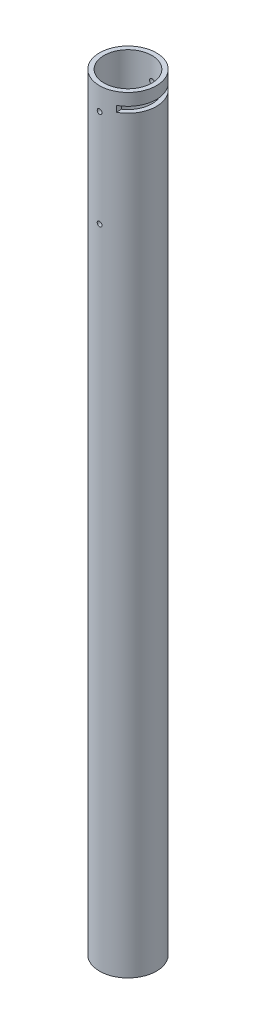
SolidWorks part; units mm, degrees
ref_plane "Front Plane" through (0, 0, 0) normal (0, 0, 1) x (1, 0, 0)
ref_plane "Top Plane" through (0, 0, 0) normal (0, 1, 0) x (1, 0, 0)
ref_plane "Right Plane" through (0, 0, 0) normal (1, 0, 0) x (0, 0, -1)
sketch "Sketch1" plane through (0, 0, 0) normal (0, 1, 0) x (1, 0, 0)
  circle A0 centre (0, 0) radius 30.1625
  circle A1 centre (0, 0) radius 25.4
  dimension "D1" = 60.325
  dimension "D2" = 50.8
extrude "Boss-Extrude1" add sketch "Sketch1" along normal blind 812.8
sketch "Sketch4" plane through (0, 0, 0) normal (0, 0, 1) x (1, 0, 0)
  line L0 (30.1625, 812.8) -> (30.1625, 800.1)
  line L1 (30.1625, 0) -> (30.1625, 812.8) construction
  line L3 (30.1625, 800.1) -> (14.2875, 800.1)
  line L6 (14.2875, 800.1) -> (14.2875, 793.75)
  line L8 (14.2875, 793.75) -> (30.1625, 793.75)
  line L9 (30.1625, 793.75) -> (30.1625, 800.1)
  line L10 (0, 812.8) -> (0, 788.9875) construction
  line L11 (25.4, 812.8) -> (-25.4, 812.8) construction
  line L12 (0, 788.9875) -> (0, 685.8) construction
  line L13 (30.1625, 812.8) -> (-30.1625, 812.8) construction
  line L14 (14.2875, 796.925) -> (30.1625, 796.925) construction
  circle A2 centre (0, 788.9875) radius 2.54
  circle A3 centre (0, 685.8) radius 2.54
  dimension "D4" = 5.08
  dimension "D1" = 6.35
  dimension "D2" = 15.875
  dimension "D3" = 15.875
  dimension "D5" = 23.8125
  dimension "D6" = 127
extrude "Cut-Extrude2" cut sketch "Sketch4" against normal through all both and the other way through all contours A3 | A2 | L8 L9 L3 L6
